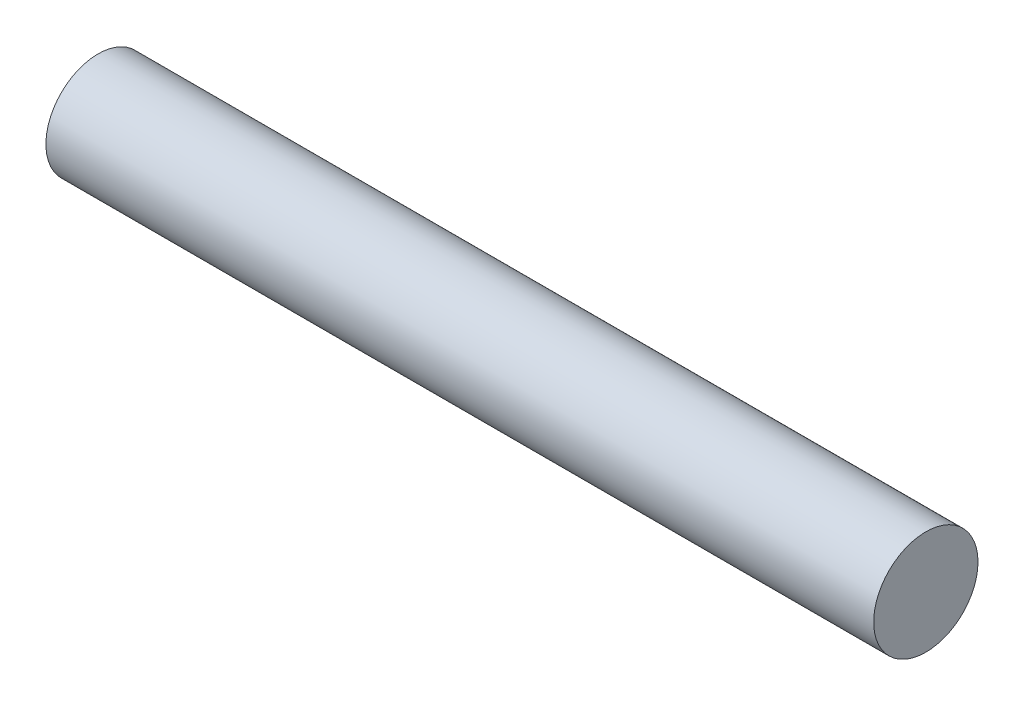
SolidWorks part; units mm, degrees
material "6061 Alloy"
ref_plane "Front Plane" through (0, 0, 0) normal (0, 0, 1) x (1, 0, 0)
ref_plane "Top Plane" through (0, 0, 0) normal (0, 1, 0) x (1, 0, 0)
ref_plane "Right Plane" through (0, 0, 0) normal (1, 0, 0) x (0, 0, -1)
sketch "Sketch1" plane through (0, 0, 0) normal (1, 0, 0) x (0, 0, -1)
  circle A0 centre (0, 0) radius 3
  dimension "D1" = 6
extrude "Boss-Extrude1" add sketch "Sketch1" along normal blind 47.6
